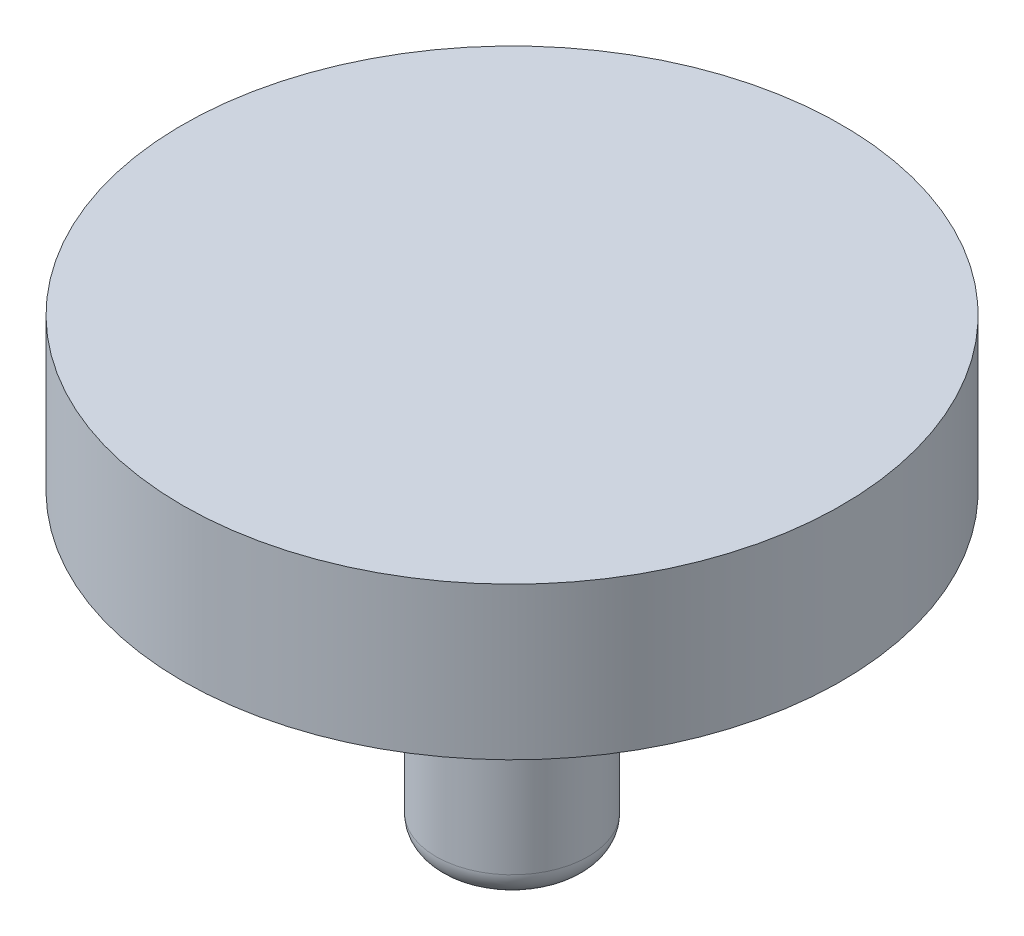
SolidWorks part; units mm, degrees
ref_plane "Front Plane" through (0, 0, 0) normal (0, 0, 1) x (1, 0, 0)
ref_plane "Top Plane" through (0, 0, 0) normal (0, 1, 0) x (1, 0, 0)
ref_plane "Right Plane" through (0, 0, 0) normal (1, 0, 0) x (0, 0, -1)
sketch "Sketch1" plane through (0, 0, 0) normal (0, 1, 0) x (1, 0, 0)
  circle A0 centre (0, 0) radius 6.5
  dimension "D1" = 13
sketch "Sketch2" plane through (0, 0, 0) normal (0, 1, 0) x (1, 0, 0)
  circle A0 centre (0, 0) radius 1.5
  dimension "D1" = 3
extrude "Boss-Extrude1" add sketch "Sketch1" along normal blind 3
extrude "Boss-Extrude2" add sketch "Sketch2" against normal blind 6
fillet "Fillet1" radius 0.5 1 edges at (0, -6, 1.5)
